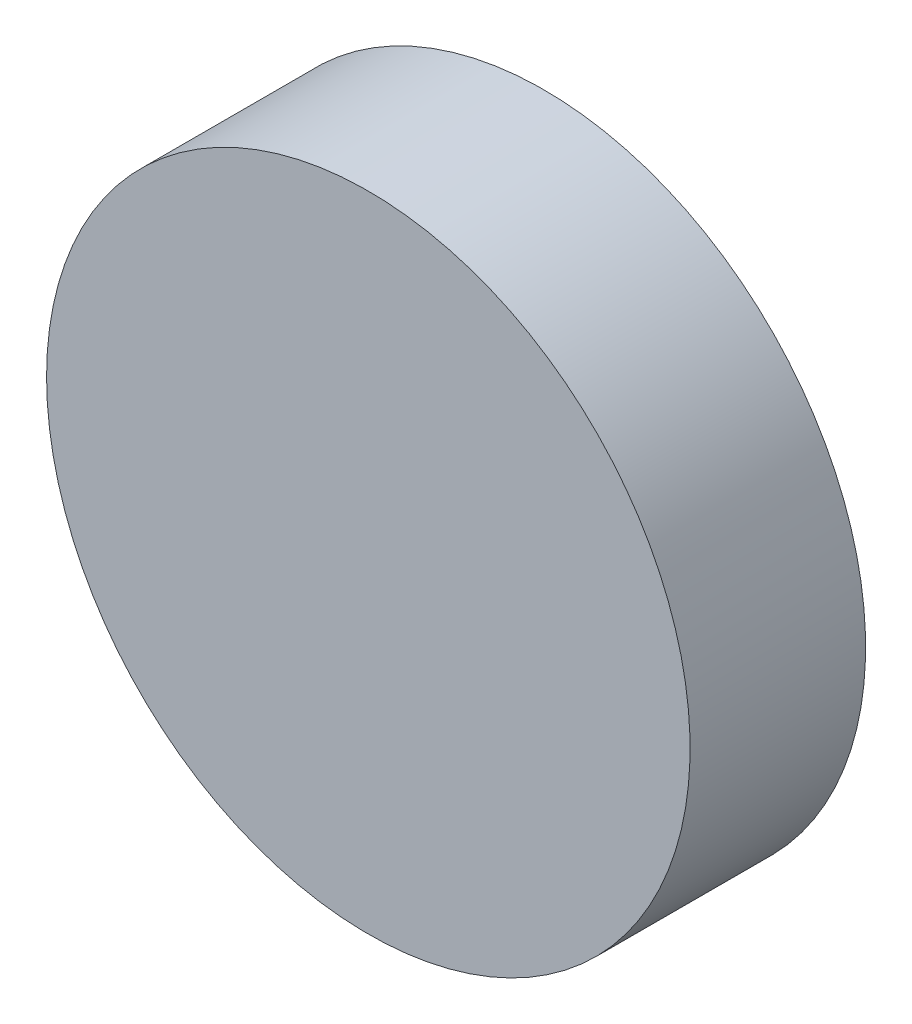
SolidWorks part; units mm, degrees
ref_plane "Front Plane" through (0, 0, 0) normal (0, 0, 1) x (1, 0, 0)
ref_plane "Top Plane" through (0, 0, 0) normal (0, 1, 0) x (1, 0, 0)
ref_plane "Right Plane" through (0, 0, 0) normal (1, 0, 0) x (0, 0, -1)
sketch "Sketch1" plane through (0, 0, 0) normal (0, 0, 1) x (1, 0, 0)
  circle A0 centre (0, 0) radius 8.7312
  dimension "D1" = 17.4625
extrude "Boss-Extrude1" add sketch "Sketch1" along normal blind 4.7625
